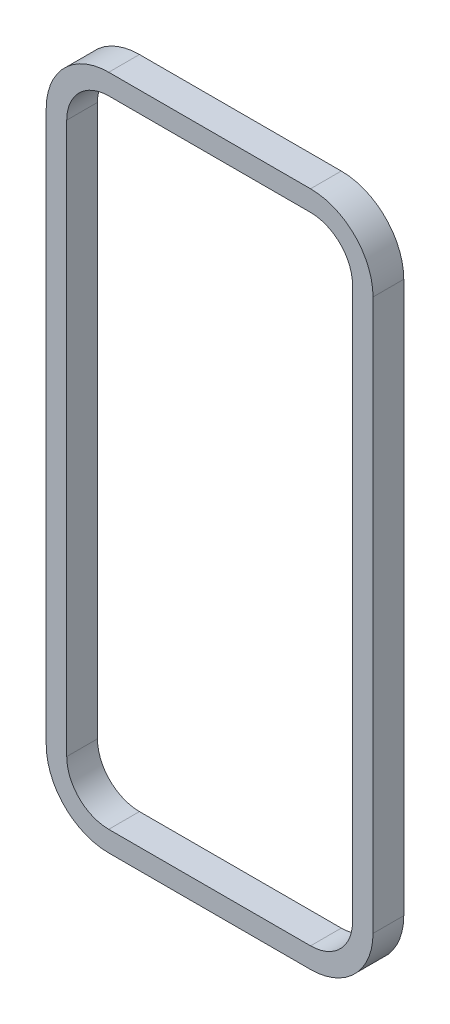
SolidWorks part; units mm, degrees
ref_plane "Front Plane" through (0, 0, 0) normal (1, 0, 0) x (0, 1, 0)
ref_plane "Top Plane" through (0, 0, 0) normal (0, 0, 1) x (0, 1, 0)
ref_plane "Right Plane" through (0, 0, 0) normal (0, 1, 0) x (-1, 0, 0)
sketch "Sketch1" plane through (0, 0, 0) normal (0, 0, 1) x (0, 1, 0)
  line L0 (-26.9, 13.95) -> (26.9, 13.95)
  line L1 (-26.9, -13.85) -> (26.9, -13.85) construction
  line L2 (-30.9, -9.85) -> (-30.9, 9.85) construction
  line L3 (-26.9, 13.85) -> (26.9, 13.85) construction
  line L4 (30.9, -9.85) -> (30.9, 9.85) construction
  line L5 (-30.9, -13.85) -> (30.9, 13.85) construction
  line L6 (-30.9, 13.85) -> (30.9, -13.85) construction
  line L7 (31, -9.85) -> (31, 9.85)
  line L8 (-26.9, -13.95) -> (26.9, -13.95)
  line L9 (-31, -9.85) -> (-31, 9.85)
  line L10 (-26.9, 15.95) -> (26.9, 15.95)
  line L11 (33, -9.85) -> (33, 9.85)
  line L12 (-26.9, -15.95) -> (26.9, -15.95)
  line L13 (-33, -9.85) -> (-33, 9.85)
  arc A0 (-30.9, 9.85) -> (-26.9, 13.85) centre (-26.9, 9.85) cw construction
  arc A1 (-26.9, -13.85) -> (-30.9, -9.85) centre (-26.9, -9.85) cw construction
  arc A2 (26.9, -13.85) -> (30.9, -9.85) centre (26.9, -9.85) ccw construction
  arc A3 (26.9, 13.85) -> (30.9, 9.85) centre (26.9, 9.85) cw construction
  arc A4 (26.9, 13.95) -> (31, 9.85) centre (26.9, 9.85) cw
  arc A5 (26.9, -13.95) -> (31, -9.85) centre (26.9, -9.85) ccw
  arc A6 (-26.9, -13.95) -> (-31, -9.85) centre (-26.9, -9.85) cw
  arc A7 (-31, 9.85) -> (-26.9, 13.95) centre (-26.9, 9.85) cw
  arc A8 (26.9, 15.95) -> (33, 9.85) centre (26.9, 9.85) cw
  arc A9 (26.9, -15.95) -> (33, -9.85) centre (26.9, -9.85) ccw
  arc A10 (-26.9, -15.95) -> (-33, -9.85) centre (-26.9, -9.85) cw
  arc A11 (-33, 9.85) -> (-26.9, 15.95) centre (-26.9, 9.85) cw
  point P0 (0, 0)
  dimension "D3" = 4
  dimension "D1" = 61.8
  dimension "D2" = 27.7
  dimension "D4" = 0.1
  dimension "D5" = 2
extrude "Boss-Extrude1" add sketch "Sketch1" along normal blind 3
